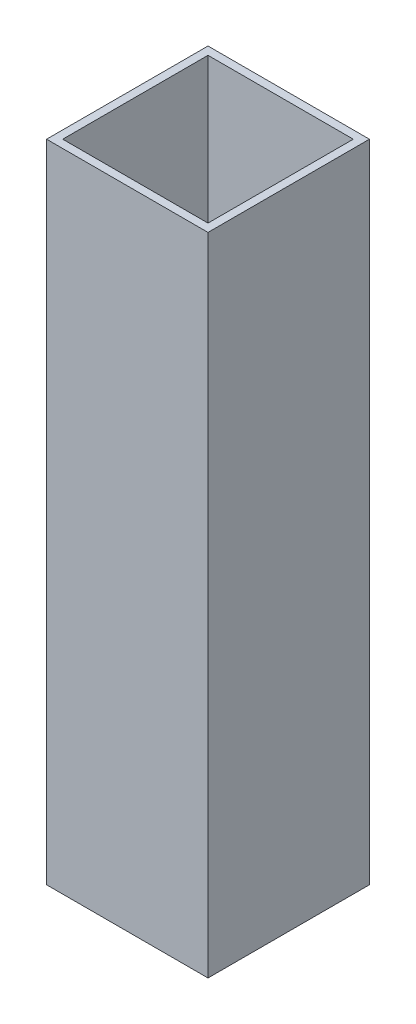
SolidWorks part; units mm, degrees
ref_plane "Front Plane" through (0, 0, 0) normal (0, 0, 1) x (1, 0, 0)
ref_plane "Top Plane" through (0, 0, 0) normal (0, 1, 0) x (1, 0, 0)
ref_plane "Right Plane" through (0, 0, 0) normal (1, 0, 0) x (0, 0, -1)
sketch "Sketch1" plane through (0, 0, 0) normal (0, 1, 0) x (1, 0, 0)
  line L1 (-12.5, 12.5) -> (12.5, 12.5)
  line L2 (-12.5, 12.5) -> (-12.5, -12.5)
  line L3 (-12.5, -12.5) -> (12.5, -12.5)
  line L4 (12.5, 12.5) -> (12.5, -12.5)
  line L5 (-12.5, 12.5) -> (12.5, -12.5) construction
  line L6 (-12.5, -12.5) -> (12.5, 12.5) construction
  line L7 (11.2504, 11.2504) -> (-11.2504, 11.2504)
  line L8 (11.2504, 11.2504) -> (11.2504, -11.2504)
  line L9 (11.2504, -11.2504) -> (-11.2504, -11.2504)
  line L10 (-11.2504, 11.2504) -> (-11.2504, -11.2504)
  line L11 (11.2504, 11.2504) -> (-11.2504, -11.2504) construction
  line L12 (11.2504, -11.2504) -> (-11.2504, 11.2504) construction
  point P0 (0, 0)
  point P6 (0, 0)
extrude "Boss-Extrude1" add sketch "Sketch1" along normal blind 100
